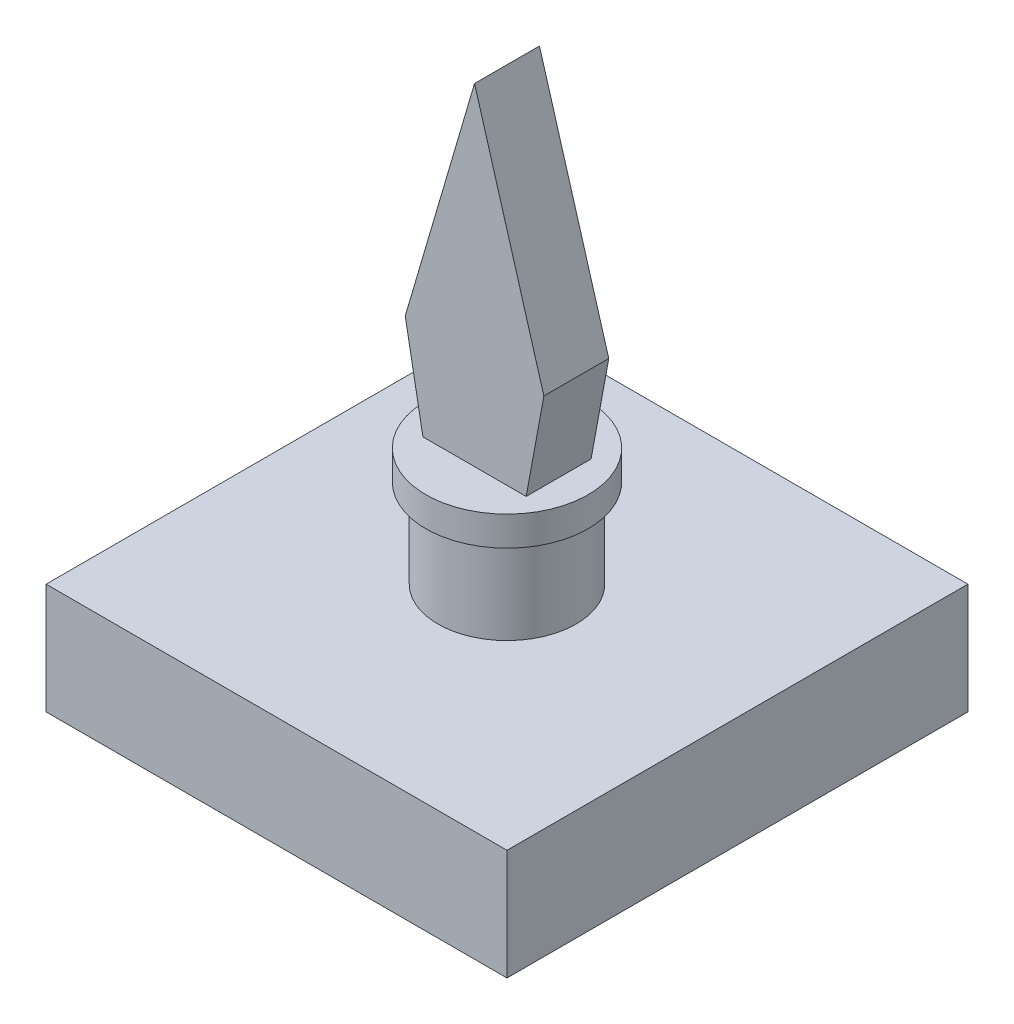
SolidWorks part; units mm, degrees
ref_plane "Front Plane" through (0, 0, 0) normal (0, 0, 1) x (1, 0, 0)
ref_plane "Top Plane" through (0, 0, 0) normal (0, 1, 0) x (1, 0, 0)
ref_plane "Right Plane" through (0, 0, 0) normal (1, 0, 0) x (0, 0, -1)
sketch "Sketch2" plane through (0, 0, 0) normal (0, 1, 0) x (1, 0, 0)
  line L1 (-6.25, -6.25) -> (6.25, -6.25)
  line L2 (-6.25, -6.25) -> (-6.25, 6.25)
  line L3 (-6.25, 6.25) -> (6.25, 6.25)
  line L4 (6.25, -6.25) -> (6.25, 6.25)
  line L5 (-6.25, -6.25) -> (6.25, 6.25) construction
  line L6 (-6.25, 6.25) -> (6.25, -6.25) construction
  point P0 (0, 0)
  dimension "D1" = 12.5
extrude "Boss-Extrude1" add sketch "Sketch2" against normal blind 3
sketch "Sketch3" plane through (0, 0, 0) normal (0, 0, 1) x (1, 0, 0)
  line L0 (0, -3) -> (0, 3.6484) construction
  line L3 (-6.25, -3) -> (6.25, -3) construction
  line L4 (0, 3.2) -> (2.2, 3.2)
  line L5 (2.2, 3.2) -> (2.2, 2.4)
  line L6 (2.2, 2.4) -> (1.875, 2.4)
  line L7 (1.875, 2.4) -> (1.875, 0)
  line L8 (-6.25, 0) -> (6.25, 0) construction
  line L9 (1.875, 0) -> (0, 0)
  line L10 (0, 3.2) -> (0, 0)
  dimension "D1" = 3.75
  dimension "D2" = 4.4
  dimension "D3" = 0.8
  dimension "D4" = 6.2
revolve "Revolve1" add sketch "Sketch3" angle 360 about L0
sketch "Sketch4" plane through (0, 0, 0) normal (0, 0, 1) x (1, 0, 0)
  line L0 (0, 0) -> (0, 12.2) construction
  line L1 (0, 12.2) -> (1.88, 5.8)
  line L2 (1.88, 5.8) -> (1.4, 3.2)
  line L3 (2.2, 3.2) -> (-2.2, 3.2) construction
  line L6 (-1.88, 5.8) -> (-1.4, 3.2)
  line L7 (0, 12.2) -> (-1.88, 5.8)
  line L8 (1.4, 3.2) -> (-1.4, 3.2)
  point P10 (0, 0)
  point P11 (0, 0)
  dimension "D1" = 3.76
  dimension "D2" = 2.6
  dimension "D3" = 9
  dimension "D4" = 2.8
extrude "Boss-Extrude2" add sketch "Sketch4" along normal mid plane 1.76
